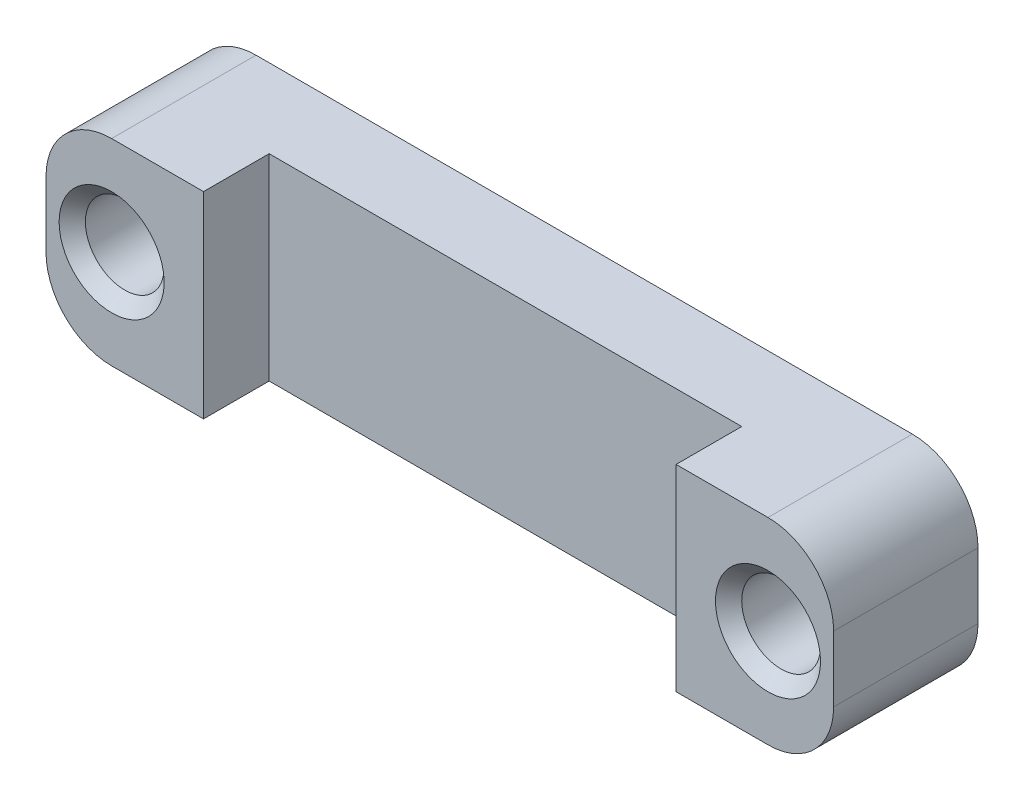
SolidWorks part; units mm, degrees
ref_plane "Alzado" through (0, 0, 0) normal (0, 0, 1) x (1, 0, 0)
ref_plane "Planta" through (0, 0, 0) normal (0, 1, 0) x (1, 0, 0)
ref_plane "Vista lateral" through (0, 0, 0) normal (1, 0, 0) x (0, 0, -1)
sketch "Croquis1" plane through (0, 0, 0) normal (0, 0, 1) x (1, 0, 0)
  line L0 (0, 0) -> (0, 15)
  line L1 (0, 15) -> (60, 15)
  line L2 (60, 15) -> (60, 0)
  line L3 (60, 0) -> (0, 0)
  circle A0 centre (5, 7.5) radius 3
  circle A1 centre (55, 7.5) radius 3
extrude "Saliente-Extruir1" add sketch "Croquis1" along normal blind 11
fillet "Redondeo1" radius 5 4 edges at (0, 0, 5.5) (60, 0, 5.5) (60, 15, 5.5) (0, 15, 5.5)
sketch "Croquis2" plane through (0, 15, 0) normal (0, 1, 0) x (1, 0, 0)
  line L2 (30, -11) -> (48, -11)
  line L8 (55, -11) -> (5, -11) construction
  line L9 (48, -11) -> (48, -6)
  line L10 (48, -6) -> (12, -6)
  line L11 (12, -6) -> (12, -11)
  line L12 (12, -11) -> (30, -11)
extrude "Cortar-Extruir1" cut sketch "Croquis2" against normal blind 21
chamfer "Chaflán1" distance 1 angle 45 2 edges at (58, 7.5, 11) (8, 7.5, 11)
